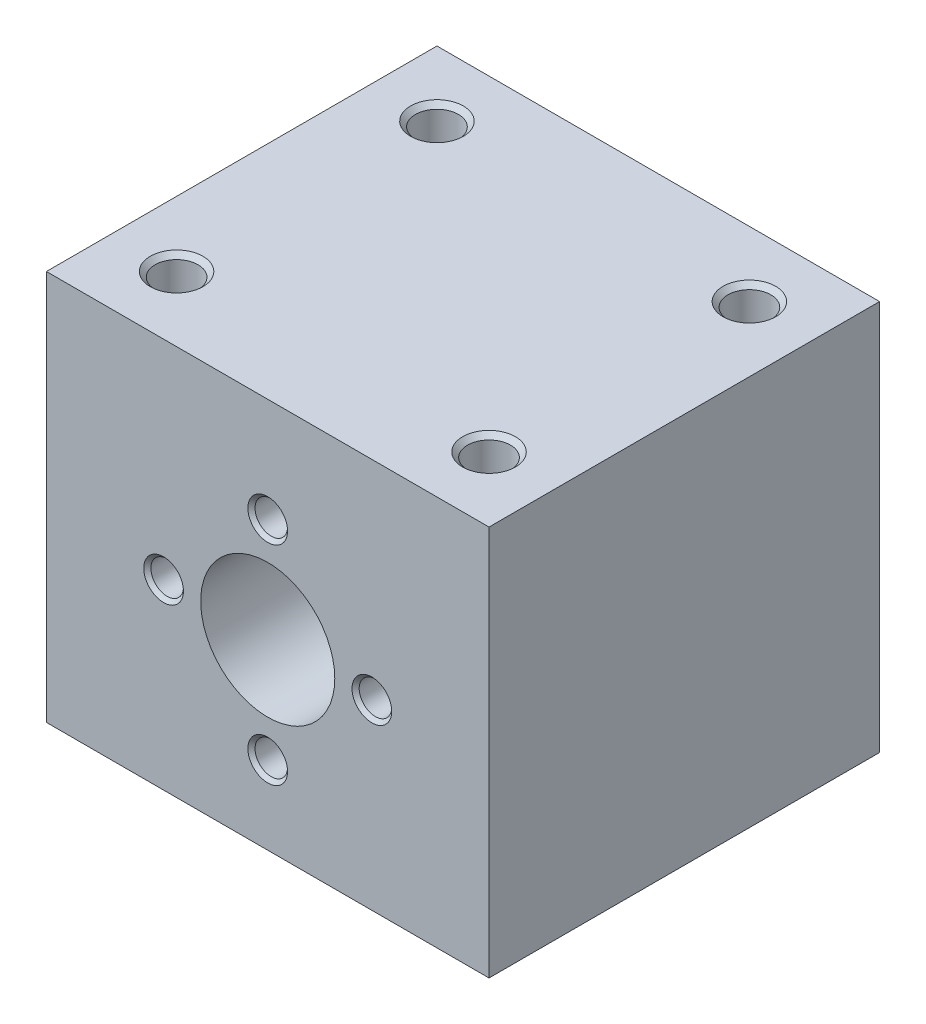
SolidWorks part; units mm, degrees
ref_plane "前视基准面" through (0, 0, 0) normal (0, 0, 1) x (1, 0, 0)
ref_plane "上视基准面" through (0, 0, 0) normal (0, 1, 0) x (1, 0, 0)
ref_plane "右视基准面" through (0, 0, 0) normal (1, 0, 0) x (0, 0, -1)
sketch "草图1" plane through (0, 0, 0) normal (0, 0, 1) x (1, 0, 0)
  line L0 (-17, -14) -> (17, -14)
  line L1 (-17, -14) -> (-17, 16)
  line L2 (17, -14) -> (17, 16)
  line L3 (-17, 16) -> (17, 16)
  line L4 (-17, -14) -> (17, 16) construction
  line L5 (17, -14) -> (-17, 16) construction
  circle A1 centre (0, 0) radius 5.15
  point P4 (0, 1)
  dimension "D1" = 14
  dimension "D4" = 10.3
  dimension "D2" = 34
  dimension "D3" = 30
extrude "凸台-拉伸1" add sketch "草图1" along normal blind 30
hole_wizard "M4 螺纹孔1" positions "草图2" profile "草图3" tap size "M4" standard "GB"
sketch "草图2" plane through (0, 16, 0) normal (0, 1, 0) x (1, 0, 0)
  line L0 (-17, -30) -> (-17, 0) construction
  line L1 (17, -30) -> (-17, -30) construction
  point P0 (-12, -5)
  point P2 (12, -5)
  point P4 (-12, -25)
  point P6 (12, -25)
  dimension "D1" = 24
  dimension "D2" = 24
  dimension "D3" = 20
  dimension "D4" = 20
  dimension "D5" = 5
  dimension "D6" = 5
  dimension "D7" = 5
  dimension "D8" = 5
sketch "草图3" plane through (-12, 16, 5) normal (1, 0, 0) x (0, 0, 1)
  line L0 (0, 0) -> (0, 13.0914)
  line L1 (0, 13.0914) -> (1.65, 12.1)
  line L2 (1.65, 12.1) -> (1.65, 0.375)
  line L3 (1.65, 0.375) -> (2.025, 0)
  line L5 (2.025, 0) -> (0, 0)
  line L6 (-1.65, 0.375) -> (-2.025, 0) construction
  line L10 (0, 13.0914) -> (-1.65, 12.1) construction
  line L11 (0, -6.35) -> (0, 107.95) construction
  dimension "螺纹孔钻头直径" = 3.3
  dimension "螺纹孔钻头深度" = 12.1
  dimension "近端锥形沉头孔直径" = 4.05
  dimension "近端锥形沉头孔角度" = 90
  dimension "导头角度" = 118
cosmetic thread "孔螺蚊线5"
cosmetic thread "孔螺蚊线6"
cosmetic thread "孔螺蚊线7"
cosmetic thread "孔螺蚊线8"
hole_wizard "M3 螺纹孔1" positions "草图4" profile "草图5" tap size "M3" standard "GB"
sketch "草图4" plane through (0, 0, 30) normal (0, 0, 1) x (1, 0, 0)
  point P0 (0, 8)
  point P2 (-8, 0)
  point P4 (8, 0)
  point P6 (0, -8)
  point P12 (0, 0)
  dimension "D1" = 16
  dimension "D2" = 8
  dimension "D3" = 8
  dimension "D4" = 16
sketch "草图5" plane through (0, 8, 30) normal (1, 0, 0) x (0, -1, 0)
  line L0 (0, 0) -> (0, 8.2511)
  line L1 (0, 8.2511) -> (1.25, 7.5)
  line L2 (1.25, 7.5) -> (1.25, 0.275)
  line L3 (1.25, 0.275) -> (1.525, 0)
  line L5 (1.525, 0) -> (0, 0)
  line L6 (-1.25, 0.275) -> (-1.525, 0) construction
  line L10 (0, 8.2511) -> (-1.25, 7.5) construction
  line L11 (0, -6.35) -> (0, 107.95) construction
  dimension "螺纹孔钻头直径" = 2.5
  dimension "螺纹孔钻头深度" = 7.5
  dimension "近端锥形沉头孔直径" = 3.05
  dimension "近端锥形沉头孔角度" = 90
  dimension "导头角度" = 118
cosmetic thread "孔螺蚊线9"
cosmetic thread "孔螺蚊线10"
cosmetic thread "孔螺蚊线11"
cosmetic thread "孔螺蚊线12"
